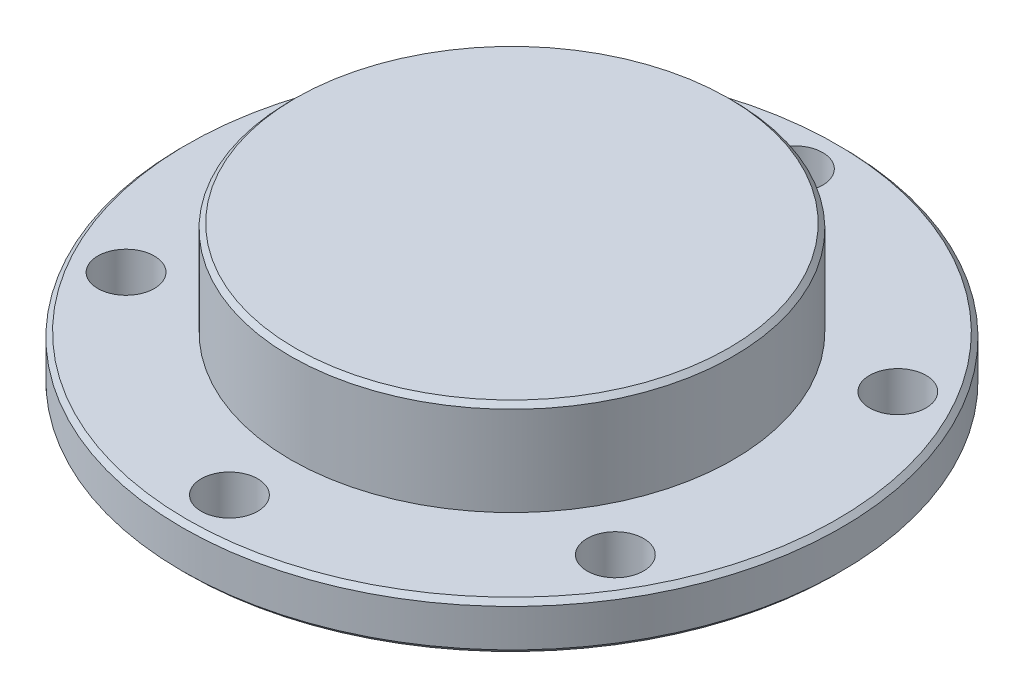
SolidWorks part; units mm, degrees
ref_plane "前视基准面" through (0, 0, 0) normal (0, 0, 1) x (1, 0, 0)
ref_plane "上视基准面" through (0, 0, 0) normal (0, 1, 0) x (1, 0, 0)
ref_plane "右视基准面" through (0, 0, 0) normal (1, 0, 0) x (0, 0, -1)
other "Configuration Table"
sketch "草图1" plane through (0, 0, 0) normal (0, 1, 0) x (1, 0, 0)
  circle A0 centre (0, 0) radius 35
  dimension "D1" = 70
extrude "凸台-拉伸1" add sketch "草图1" along normal blind 5
sketch "草图2" plane through (0, 5, 0) normal (0, 1, 0) x (1, 0, 0)
  circle A0 centre (0, 0) radius 23.5
  dimension "D1" = 47
extrude "凸台-拉伸2" add sketch "草图2" along normal blind 10
sketch "草图3" plane through (0, 0, 0) normal (0, -1, 0) x (1, 0, 0)
  circle A0 centre (0, 0) radius 20
  dimension "D1" = 40
extrude "切除-拉伸1" cut sketch "草图3" against normal blind 14
sketch "草图4" plane through (0, 5, 0) normal (0, 1, 0) x (1, 0, 0)
  circle A0 centre (0, 0) radius 30 construction
  circle A1 centre (0, 30) radius 3
  circle A2 centre (25.9808, 15) radius 3
  circle A3 centre (25.9808, -15) radius 3
  circle A4 centre (0, -30) radius 3
  circle A5 centre (-25.9808, -15) radius 3
  circle A6 centre (-25.9808, 15) radius 3
  point P18 (0, 0)
  dimension "D1" = 60
  dimension "D2" = 6
  dimension "D3" = 6
extrude "切除-拉伸2" cut sketch "草图4" against normal blind 14
fillet "圆角1" radius 0.5 4 edges at (0, 0, -20) (0, 0, 35) (0, 5, 35) (0, 15, 23.5) profile chamfer
